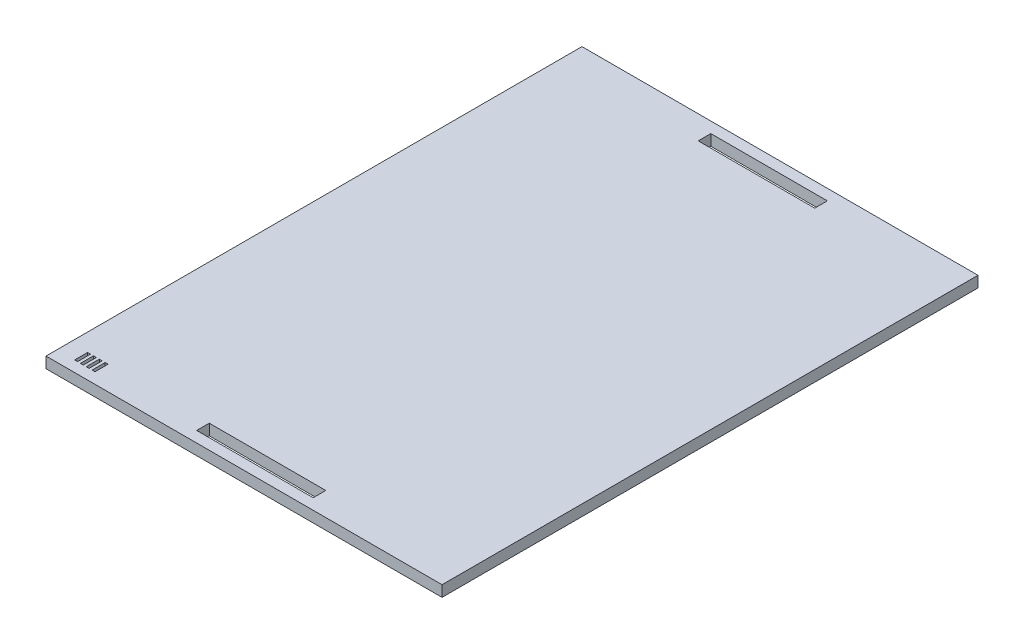
SolidWorks part; units mm, degrees
ref_plane "Front Plane" through (0, 0, 0) normal (0, 0, 1) x (1, 0, 0)
ref_plane "Top Plane" through (0, 0, 0) normal (0, 1, 0) x (1, 0, 0)
ref_plane "Right Plane" through (0, 0, 0) normal (1, 0, 0) x (0, 0, -1)
sketch "Sketch1" plane through (0, 0, 0) normal (0, 1, 0) x (1, 0, 0)
  line L0 (-53.9623, 66.4972) -> (53.9623, 66.4972) construction
  line L1 (53.9623, -73.025) -> (-53.9623, -73.025)
  line L2 (53.9623, -73.025) -> (53.9623, 73.025)
  line L3 (53.9623, 73.025) -> (-53.9623, 73.025)
  line L4 (-53.9623, -73.025) -> (-53.9623, 73.025)
  line L5 (53.9623, -73.025) -> (-53.9623, 73.025) construction
  line L6 (53.9623, 73.025) -> (-53.9623, -73.025) construction
  line L7 (-53.9623, -66.4972) -> (53.9623, -66.4972) construction
  line L8 (-53.9623, 66.4972) -> (-53.9623, -66.4972) construction
  line L9 (53.9623, 66.4972) -> (53.9623, -66.4972) construction
  line L10 (0, 66.6242) -> (0, -66.6242) construction
  line L11 (-15.875, 70.0532) -> (15.875, 70.0532)
  line L12 (-15.875, 70.0532) -> (-15.875, 66.6242)
  line L13 (-15.875, 66.6242) -> (15.875, 66.6242)
  line L14 (15.875, 70.0532) -> (15.875, 66.6242)
  line L15 (-15.875, -66.6242) -> (15.875, -66.6242)
  line L16 (-15.875, -66.6242) -> (-15.875, -70.0532)
  line L17 (-15.875, -70.0532) -> (15.875, -70.0532)
  line L18 (15.875, -66.6242) -> (15.875, -70.0532)
  line L19 (-53.9623, -70.0532) -> (53.9623, -70.0532) construction
  line L20 (-48.3448, -68.2752) -> (-47.551, -68.2752) construction
  line L21 (-49.1385, -66.4972) -> (-48.3448, -66.4972)
  line L22 (-49.1385, -66.4972) -> (-49.1385, -70.0532)
  line L23 (-49.1385, -70.0532) -> (-48.3448, -70.0532)
  line L24 (-48.3448, -66.4972) -> (-48.3448, -70.0532)
  line L25 (-47.551, -70.0532) -> (-46.7573, -70.0532)
  line L26 (-47.551, -70.0532) -> (-47.551, -66.4972)
  line L27 (-47.551, -66.4972) -> (-46.7573, -66.4972)
  line L28 (-46.7573, -70.0532) -> (-46.7573, -66.4972)
  line L29 (-46.7573, -68.2752) -> (-45.9635, -68.2752) construction
  line L30 (-45.9635, -66.4972) -> (-45.1698, -66.4972)
  line L31 (-45.9635, -66.4972) -> (-45.9635, -70.0532)
  line L32 (-45.9635, -70.0532) -> (-45.1698, -70.0532)
  line L33 (-45.1698, -66.4972) -> (-45.1698, -70.0532)
  line L34 (-45.1698, -68.2752) -> (-44.376, -68.2752) construction
  line L35 (-44.376, -66.4972) -> (-43.5823, -66.4972)
  line L36 (-44.376, -66.4972) -> (-44.376, -70.0532)
  line L37 (-44.376, -70.0532) -> (-43.5823, -70.0532)
  line L38 (-43.5823, -66.4972) -> (-43.5823, -70.0532)
  point P0 (0, 0)
  point P10 (53.9623, 0)
  point P11 (53.9623, 0)
  point P16 (0, 66.6242)
  point P17 (0, 0)
  dimension "D1" = 107.9246
  dimension "D2" = 146.05
  dimension "D3" = 132.9944
  dimension "D4" = 3.429
  dimension "D5" = 31.75
  dimension "D6" = 0.254
  dimension "D7" = 0.7937
extrude "Boss-Extrude1" add sketch "Sketch1" along normal blind 2.9972 contours L4 L1 L2 L3 L11 L14 L13 L12 L15 L18 L17 L16
